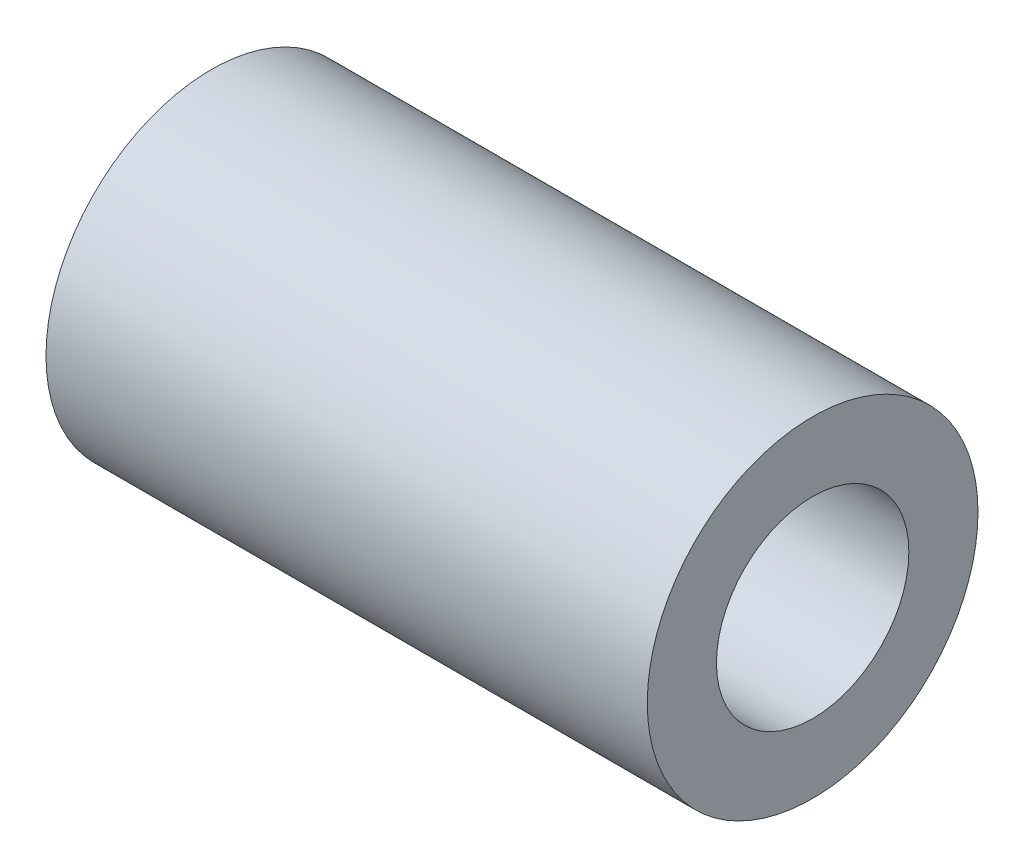
SolidWorks part; units mm, degrees
material "Copper"
ref_plane "Front Plane" through (0, 0, 0) normal (0, 0, 1) x (1, 0, 0)
ref_plane "Top Plane" through (0, 0, 0) normal (0, 1, 0) x (1, 0, 0)
ref_plane "Right Plane" through (0, 0, 0) normal (1, 0, 0) x (0, 0, -1)
sketch "Axial profile (mm)" plane through (0, 0, 0) normal (0, 0, 1) x (1, 0, 0)
  line L0 (-110, 0) -> (75, 0) construction
  line L1 (-103, 0) -> (-94, 0)
  line L2 (-94, 0) -> (-94, 3.2)
  line L3 (-94, 3.2) -> (-83, 3.2)
  line L4 (-83, 3.2) -> (-83, 5.5)
  line L5 (-83, 5.5) -> (-103, 5.5)
  line L6 (-103, 5.5) -> (-103, 0)
revolve "Full revolution" add sketch "Axial profile (mm)" angle 360 about L0
